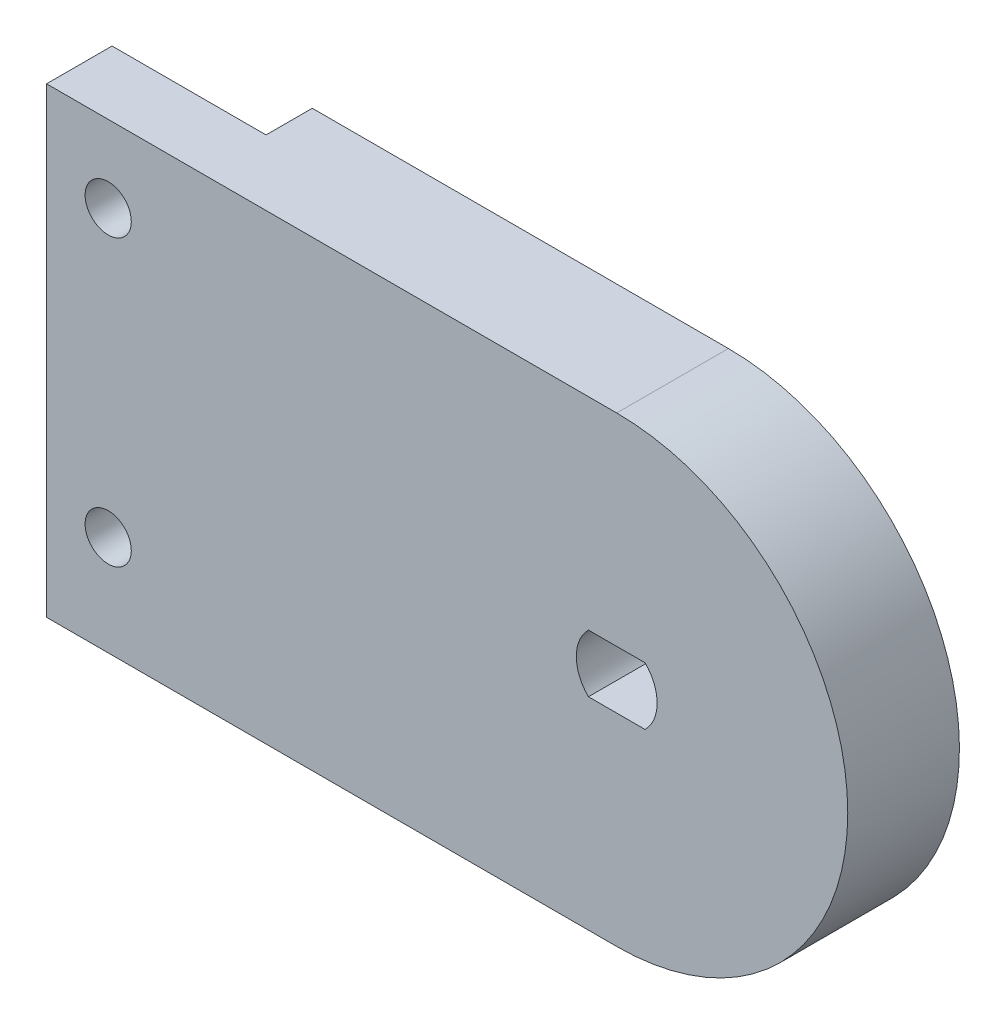
SolidWorks part; units mm, degrees
ref_plane "Front Plane" through (0, 0, 0) normal (0, 0, 1) x (1, 0, 0)
ref_plane "Top Plane" through (0, 0, 0) normal (0, 1, 0) x (1, 0, 0)
ref_plane "Right Plane" through (0, 0, 0) normal (1, 0, 0) x (0, 0, -1)
sketch "Sketch2" plane through (0, 0, -8) normal (0, 0, 1) x (1, 0, 0)
  line L0 (-25.7692, 245.1803) -> (-54.7874, 245.1803)
  line L1 (-54.7874, 245.1803) -> (-54.7874, 215.1803)
  line L2 (-54.7874, 215.1803) -> (-25.7692, 215.1803)
  arc A2 (-25.7692, 215.1803) -> (-25.7692, 245.1803) centre (-25.7692, 230.1803) ccw
  dimension "D1" = 29.0182
extrude "Boss-Extrude1" add sketch "Sketch2" along normal blind 8
sketch "Sketch3" plane through (0, 0, -28) normal (0, 0, -1) x (-1, 0, 0)
  line L3 (25.7692, 215.1803) -> (54.7874, 215.1803)
  line L4 (54.7874, 215.1803) -> (54.7874, 245.1803)
  line L5 (54.7874, 245.1803) -> (25.7692, 245.1803)
  line L6 (25.7692, 215.1803) -> (54.7874, 215.1803)
  line L7 (54.7874, 215.1803) -> (54.7874, 245.1803)
  line L8 (54.7874, 245.1803) -> (25.7692, 245.1803)
  arc A1 (25.7692, 245.1803) -> (25.7692, 215.1803) centre (25.7692, 230.1803) ccw
  arc A2 (25.7692, 245.1803) -> (25.7692, 215.1803) centre (25.7692, 230.1803) ccw
  dimension "D1" = 0
extrude "Boss-Extrude2" add sketch "Sketch3" along normal blind 8 separate body
sketch "Sketch4" plane through (-54.7874, 0, 0) normal (-1, 0, 0) x (0, 0, 1)
  line L1 (-36, 245.1803) -> (0, 245.1803)
  line L2 (-36, 245.1803) -> (-36, 215.1803)
  line L3 (-36, 215.1803) -> (0, 215.1803)
  line L4 (0, 245.1803) -> (0, 215.1803)
extrude "Boss-Extrude3" add sketch "Sketch4" along normal blind 8
sketch "Sketch5" plane through (-62.7874, 0, 0) normal (-1, 0, 0) x (0, 0, 1)
  circle A1 centre (-18, 230.1803) radius 7
  circle A2 centre (-18, 230.1803) radius 5
extrude "Boss-Extrude4" add sketch "Sketch5" along normal blind 10
chamfer "Chamfer1" distance 3 angle 45 1 edges at (-62.7874, 230.1803, -11)
sketch "Sketch6" plane through (0, 0, -36) normal (0, 0, -1) x (-1, 0, 0)
  line L0 (23.9321, 232.0553) -> (27.6063, 232.0553)
  line L1 (23.9321, 228.3053) -> (27.6063, 228.3053)
  arc A0 (23.9321, 232.0553) -> (23.9321, 228.3053) centre (25.7692, 230.1803) ccw
  arc A1 (27.6063, 228.3053) -> (27.6063, 232.0553) centre (25.7692, 230.1803) ccw
  dimension "D1" = 1.875
  dimension "D2" = 3.75
extrude "Cut-Extrude1" cut sketch "Sketch6" against normal up to surface (36 mm away) up to face at (-40.5283, 230.1803, 0)
sketch "Sketch7" plane through (-62.7874, 0, 0) normal (-1, 0, 0) x (0, 0, 1)
  line L0 (0, 215.1803) -> (0, 218.1803)
  line L1 (0, 215.1803) -> (0, 245.1803) construction
  line L2 (0, 215.1803) -> (-3, 215.1803)
  line L3 (-36, 215.1803) -> (0, 215.1803) construction
  line L4 (-18, 215.1803) -> (-18, 245.1803) construction
  line L5 (0, 245.1803) -> (-36, 245.1803) construction
  line L6 (-36, 215.1803) -> (-33, 215.1803)
  line L7 (-36, 215.1803) -> (-36, 218.1803)
  arc A0 (0, 218.1803) -> (-3, 215.1803) centre (-3, 218.1803) cw
  arc A1 (-36, 218.1803) -> (-33, 215.1803) centre (-33, 218.1803) ccw
extrude "Cut-Extrude2" cut sketch "Sketch7" against normal through all
sketch "Sketch8" plane through (0, 215.1803, 0) normal (0, -1, 0) x (1, 0, 0)
  line L0 (-54.7874, -8) -> (-25.7692, -8) construction
  line L1 (-56.7874, -28) -> (-39.7874, -28)
  line L2 (-56.7874, -28) -> (-56.7874, -8)
  line L3 (-56.7874, -8) -> (-39.7874, -8)
  line L4 (-39.7874, -28) -> (-39.7874, -8)
extrude "Boss-Extrude5" add sketch "Sketch8" against normal blind 7
sketch "Sketch10" plane through (0, 0, -28) normal (0, 0, 1) x (1, 0, 0)
  line L5 (-54.7874, 222.1803) -> (-39.7874, 222.1803)
  line L6 (-39.7874, 222.1803) -> (-39.7874, 215.1803)
  line L7 (-39.7874, 215.1803) -> (-25.7692, 215.1803)
  line L8 (-25.7692, 245.1803) -> (-54.7874, 245.1803)
  line L9 (-54.7874, 245.1803) -> (-54.7874, 222.1803)
  line L10 (-54.7874, 222.1803) -> (-39.7874, 222.1803)
  line L11 (-39.7874, 222.1803) -> (-39.7874, 215.1803)
  line L12 (-39.7874, 215.1803) -> (-25.7692, 215.1803)
  line L13 (-25.7692, 245.1803) -> (-54.7874, 245.1803)
  line L14 (-54.7874, 245.1803) -> (-54.7874, 222.1803)
  arc A1 (-25.7692, 215.1803) -> (-25.7692, 245.1803) centre (-25.7692, 230.1803) ccw
  arc A2 (-25.7692, 215.1803) -> (-25.7692, 245.1803) centre (-25.7692, 230.1803) ccw
  dimension "D1" = 0
extrude "Cut-Extrude3" cut sketch "Sketch10" against normal blind 0.75
sketch "Sketch11" plane through (0, 0, -8) normal (0, 0, -1) x (-1, 0, 0)
  line L5 (25.7692, 215.1803) -> (39.7874, 215.1803)
  line L6 (39.7874, 215.1803) -> (39.7874, 222.1803)
  line L7 (39.7874, 222.1803) -> (54.7874, 222.1803)
  line L8 (54.7874, 222.1803) -> (54.7874, 245.1803)
  line L9 (54.7874, 245.1803) -> (25.7692, 245.1803)
  line L10 (25.7692, 215.1803) -> (39.7874, 215.1803)
  line L11 (39.7874, 215.1803) -> (39.7874, 222.1803)
  line L12 (39.7874, 222.1803) -> (54.7874, 222.1803)
  line L13 (54.7874, 222.1803) -> (54.7874, 245.1803)
  line L14 (54.7874, 245.1803) -> (25.7692, 245.1803)
  arc A1 (25.7692, 245.1803) -> (25.7692, 215.1803) centre (25.7692, 230.1803) ccw
  arc A2 (25.7692, 245.1803) -> (25.7692, 215.1803) centre (25.7692, 230.1803) ccw
  dimension "D1" = 0
extrude "Cut-Extrude4" cut sketch "Sketch11" against normal blind 0.75
sketch "Sketch12" plane through (-62.7874, 0, 0) normal (-1, 0, 0) x (0, 0, 1)
  line L1 (-23.75, 242.6803) -> (-12.25, 242.6803)
  line L2 (-24.75, 241.6803) -> (-24.75, 239.1803)
  line L3 (-23.75, 238.1803) -> (-12.25, 238.1803)
  line L4 (-7.25, 245.1803) -> (-28.75, 245.1803)
  line L5 (-7.25, 222.1803) -> (-7.25, 245.1803)
  line L6 (-28.75, 222.1803) -> (-7.25, 222.1803)
  line L7 (-28.75, 245.1803) -> (-28.75, 222.1803)
  line L8 (-7.25, 245.1803) -> (-28.75, 245.1803) construction
  line L9 (-7.25, 222.1803) -> (-7.25, 245.1803) construction
  line L10 (-28.75, 222.1803) -> (-7.25, 222.1803) construction
  line L11 (-28.75, 245.1803) -> (-28.75, 222.1803) construction
  line L12 (-11.25, 241.6803) -> (-11.25, 239.1803)
  arc A0 (-12.25, 238.1803) -> (-11.25, 239.1803) centre (-12.25, 239.1803) ccw
  arc A1 (-12.25, 242.6803) -> (-11.25, 241.6803) centre (-12.25, 241.6803) cw
  arc A2 (-23.75, 242.6803) -> (-24.75, 241.6803) centre (-23.75, 241.6803) ccw
  arc A3 (-24.75, 239.1803) -> (-23.75, 238.1803) centre (-23.75, 239.1803) ccw
  point P10 (-11.25, 238.1803)
  point P13 (-11.25, 242.6803)
  dimension "D6" = 1
  dimension "D1" = 0
extrude "Cut-Extrude5" cut sketch "Sketch12" against normal through all both and the other way through all
sketch "Sketch13" plane through (0, 0, -36) normal (0, 0, -1) x (-1, 0, 0)
  line L1 (52.7874, 245.1803) -> (65.2203, 245.1803)
  line L2 (52.7874, 245.1803) -> (52.7874, 215.1803)
  line L3 (52.7874, 215.1803) -> (65.2203, 215.1803)
  line L4 (65.2203, 245.1803) -> (65.2203, 215.1803)
extrude "Cut-Extrude6" cut sketch "Sketch13" against normal blind 3
sketch "Sketch14" plane through (0, 0, 0) normal (0, 0, 1) x (1, 0, 0)
  line L4 (-52.7874, 245.1803) -> (-62.7874, 245.1803)
  line L5 (-52.7874, 215.1803) -> (-52.7874, 245.1803)
  line L6 (-62.7874, 215.1803) -> (-52.7874, 215.1803)
  line L7 (-62.7874, 245.1803) -> (-62.7874, 215.1803)
  line L8 (-52.7874, 245.1803) -> (-62.7874, 245.1803)
  line L9 (-52.7874, 215.1803) -> (-52.7874, 245.1803)
  line L10 (-62.7874, 215.1803) -> (-52.7874, 215.1803)
  line L11 (-62.7874, 245.1803) -> (-62.7874, 215.1803)
  dimension "D1" = 0
extrude "Cut-Extrude7" cut sketch "Sketch14" against normal blind 3
sketch "Sketch15" plane through (0, 0, 0) normal (0, 0, 1) x (1, 0, 0)
  spline S0 degree 3 poles (-58.7873, 241.6803) (-61.7873, 241.6803) (-61.7873, 238.6803) (-58.7873, 238.6803) (-55.7873, 238.6803) (-55.7873, 241.6803) (-58.7873, 241.6803) (-61.7873, 241.6803) (-61.7873, 238.6803) knots -0.5 0 0 0 0.5 0.5 0.5 1 1 1 1.5 1.5 1.5 weights 1 0.333333 0.333333 1 0.333333 0.333333 1 0.333333 0.333333 only from (-58.7873, 241.6803) to (-58.7873, 241.6803) construction
  spline S1 degree 3 poles (-58.7873, 223.18) (-61.7873, 223.18) (-61.7873, 220.18) (-58.7873, 220.18) (-55.7873, 220.18) (-55.7873, 223.18) (-58.7873, 223.18) (-61.7873, 223.18) (-61.7873, 220.18) knots -0.5 0 0 0 0.5 0.5 0.5 1 1 1 1.5 1.5 1.5 weights 1 0.333333 0.333333 1 0.333333 0.333333 1 0.333333 0.333333 only from (-58.7873, 223.18) to (-58.7873, 223.18) construction
  spline S2 degree 3 poles (-58.7873, 241.6803) (-61.7873, 241.6803) (-61.7873, 238.6803) (-58.7873, 238.6803) (-55.7873, 238.6803) (-55.7873, 241.6803) (-58.7873, 241.6803) (-61.7873, 241.6803) (-61.7873, 238.6803) knots -0.5 0 0 0 0.5 0.5 0.5 1 1 1 1.5 1.5 1.5 weights 1 0.333333 0.333333 1 0.333333 0.333333 1 0.333333 0.333333 only from (-58.7873, 241.6803) to (-58.7873, 241.6803)
  spline S3 degree 3 poles (-58.7873, 223.18) (-61.7873, 223.18) (-61.7873, 220.18) (-58.7873, 220.18) (-55.7873, 220.18) (-55.7873, 223.18) (-58.7873, 223.18) (-61.7873, 223.18) (-61.7873, 220.18) knots -0.5 0 0 0 0.5 0.5 0.5 1 1 1 1.5 1.5 1.5 weights 1 0.333333 0.333333 1 0.333333 0.333333 1 0.333333 0.333333 only from (-58.7873, 223.18) to (-58.7873, 223.18)
extrude "Cut-Extrude8" cut sketch "Sketch15" against normal up to surface (36 mm away)
sketch "Sketch16" plane through (0, 0, 0) normal (0, 0, 1) x (1, 0, 0)
  line L1 (-8.857, 211.1546) -> (-76.0917, 211.1546)
  line L2 (-8.857, 211.1546) -> (-8.857, 248.0517)
  line L3 (-8.857, 248.0517) -> (-76.0917, 248.0517)
  line L4 (-76.0917, 211.1546) -> (-76.0917, 248.0517)
extrude "Cut-Extrude9" cut sketch "Sketch16" against normal up to surface (28.75 mm away) up to face at (-37.6147, 227.5136, -28.75)
